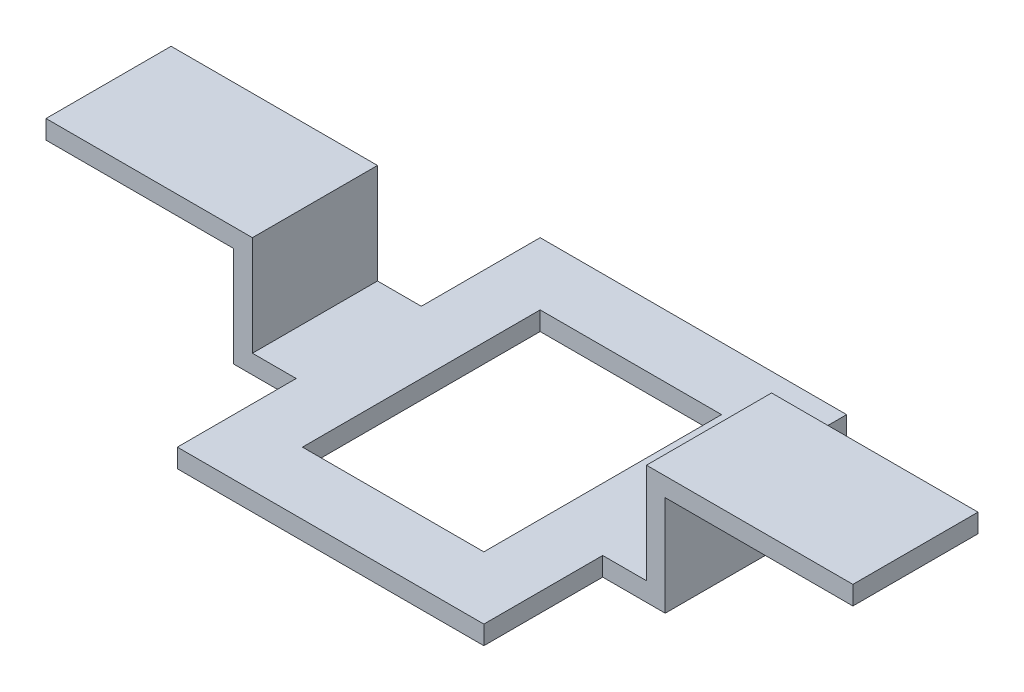
SolidWorks part; units mm, degrees
ref_plane "Front Plane" through (0, 0, 0) normal (0, 0, 1) x (1, 0, 0)
ref_plane "Top Plane" through (0, 0, 0) normal (0, 1, 0) x (1, 0, 0)
ref_plane "Right Plane" through (0, 0, 0) normal (1, 0, 0) x (0, 0, -1)
sketch "Sketch2" plane through (0, 0, 0) normal (0, 1, 0) x (1, 0, 0)
  line L1 (-24.5, 29) -> (24.5, 29)
  line L2 (-24.5, 29) -> (-24.5, -29)
  line L3 (-24.5, -29) -> (24.5, -29)
  line L4 (24.5, 29) -> (24.5, -29)
  line L5 (-24.5, 29) -> (24.5, -29) construction
  line L6 (-24.5, -29) -> (24.5, 29) construction
  point P0 (0, 0)
  dimension "D1" = 58
  dimension "D2" = 49
extrude "Boss-Extrude1" add sketch "Sketch2" along normal blind 3
sketch "Sketch3" plane through (0, 3, 0) normal (0, 1, 0) x (1, 0, 0)
  line L1 (-14.5, 19) -> (14.5, 19)
  line L2 (-14.5, 19) -> (-14.5, -19)
  line L3 (-14.5, -19) -> (14.5, -19)
  line L4 (14.5, 19) -> (14.5, -19)
  line L5 (-14.5, 19) -> (14.5, -19) construction
  line L6 (-14.5, -19) -> (14.5, 19) construction
  point P0 (0, 0)
  dimension "D1" = 38
  dimension "D2" = 29
extrude "Cut-Extrude1" cut sketch "Sketch3" against normal blind 3
sketch "Sketch4" plane through (-24.5, 0, 0) normal (-1, 0, 0) x (0, 0, 1)
  line L0 (-10, 0) -> (10, 0)
  line L1 (-29, 0) -> (29, 0) construction
  line L2 (10, 0) -> (10, 3)
  line L3 (-29, 3) -> (29, 3) construction
  line L4 (10, 3) -> (-10, 3)
  line L5 (-10, 3) -> (-10, 0)
  point P6 (0, 0)
  dimension "D1" = 20
extrude "Boss-Extrude2" add sketch "Sketch4" along normal blind 10
sketch "Sketch5" plane through (0, 3, 0) normal (0, 1, 0) x (1, 0, 0)
  line L0 (-34.5, -10) -> (-24.5, -10) construction
  line L1 (-34.5, 10) -> (-31.5, 10)
  line L2 (-34.5, 10) -> (-34.5, -10)
  line L3 (-34.5, -10) -> (-31.5, -10)
  line L4 (-31.5, 10) -> (-31.5, -10)
  dimension "D1" = 3
extrude "Boss-Extrude3" add sketch "Sketch5" along normal blind 16
sketch "Sketch7" plane through (-34.5, 0, 0) normal (-1, 0, 0) x (0, 0, 1)
  line L0 (10, 0) -> (10, 19) construction
  line L1 (-10, 19) -> (10, 19)
  line L2 (-10, 19) -> (-10, 16)
  line L3 (-10, 16) -> (10, 16)
  line L4 (10, 19) -> (10, 16)
  dimension "D1" = 3
extrude "Boss-Extrude4" add sketch "Sketch7" along normal blind 30
mirror "Mirror1" about plane through (0, 0, 0) normal (1, 0, 0) of "Boss-Extrude2", "Boss-Extrude3", "Boss-Extrude4"
